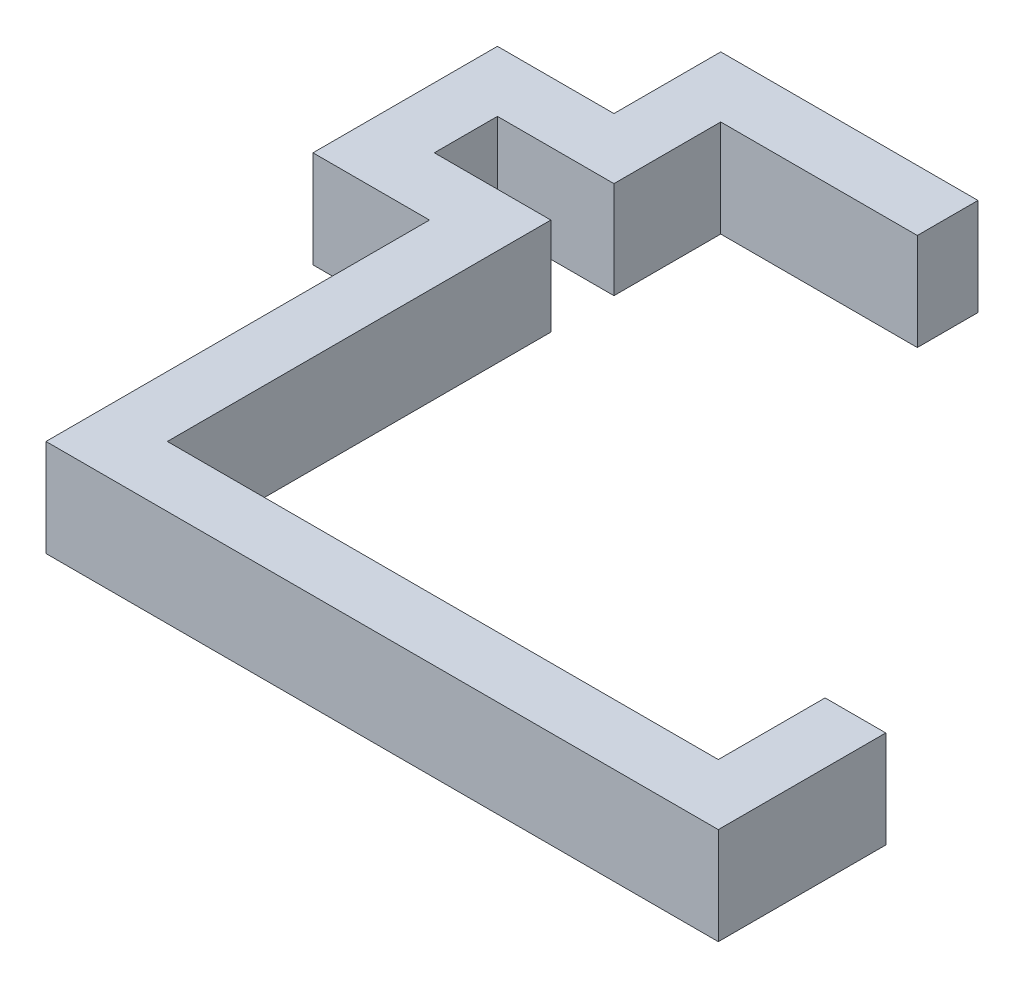
SolidWorks part; units mm, degrees
ref_plane "Front Plane" through (0, 0, 0) normal (0, 0, 1) x (1, 0, 0)
ref_plane "Top Plane" through (0, 0, 0) normal (0, 1, 0) x (1, 0, 0)
ref_plane "Right Plane" through (0, 0, 0) normal (1, 0, 0) x (0, 0, -1)
sketch "Sketch1" plane through (0, 0, 0) normal (0, 1, 0) x (1, 0, 0)
  line L0 (0, 0) -> (-22.7, 0)
  line L1 (-22.7, 0) -> (-22.7, 15.8)
  line L2 (-22.7, 15.8) -> (-27.5, 15.8)
  line L3 (-27.5, 15.8) -> (-27.5, 18.4)
  line L4 (-27.5, 18.4) -> (-22.7, 18.4)
  line L5 (-22.7, 18.4) -> (-22.7, 22.8)
  line L6 (-22.7, 22.8) -> (-14.6, 22.8)
  line L7 (-14.6, 22.8) -> (-14.6, 25.3)
  line L8 (-14.6, 25.3) -> (-25.2, 25.3)
  line L9 (-25.2, 25.3) -> (-25.2, 20.9)
  line L10 (-25.2, 20.9) -> (-30, 20.9)
  line L11 (-30, 20.9) -> (-30, 13.3)
  line L12 (-30, 13.3) -> (-25.2, 13.3)
  line L13 (-25.2, 13.3) -> (-25.2, -2.5)
  line L14 (-25.2, -2.5) -> (2.5, -2.5)
  line L15 (2.5, -2.5) -> (2.5, 4.4)
  line L16 (2.5, 4.4) -> (0, 4.4)
  line L17 (0, 4.4) -> (0, 0)
  line L18 (-20.3849, 22.8) -> (-20.3849, 25.3) construction
  line L19 (-30, 17.4855) -> (-27.5, 17.4855) construction
  line L20 (-26.3183, 18.4) -> (-26.3183, 20.9) construction
  line L21 (-26.6067, 13.3) -> (-26.6067, 15.8) construction
  line L22 (-25.2, 16.4649) -> (-22.7, 16.4649) construction
  line L23 (-18.3967, -2.5) -> (-18.3967, 0) construction
  line L25 (0, 4.1412) -> (2.5, 4.1412) construction
  dimension "D1" = 8.1
  dimension "D2" = 4.4
  dimension "D3" = 4.8
  dimension "D4" = 2.5
  dimension "D5" = 2.6
  dimension "D6" = 15.8
  dimension "D7" = 22.7
  dimension "D8" = 4.4
extrude "Boss-Extrude1" add sketch "Sketch1" along normal blind 4
